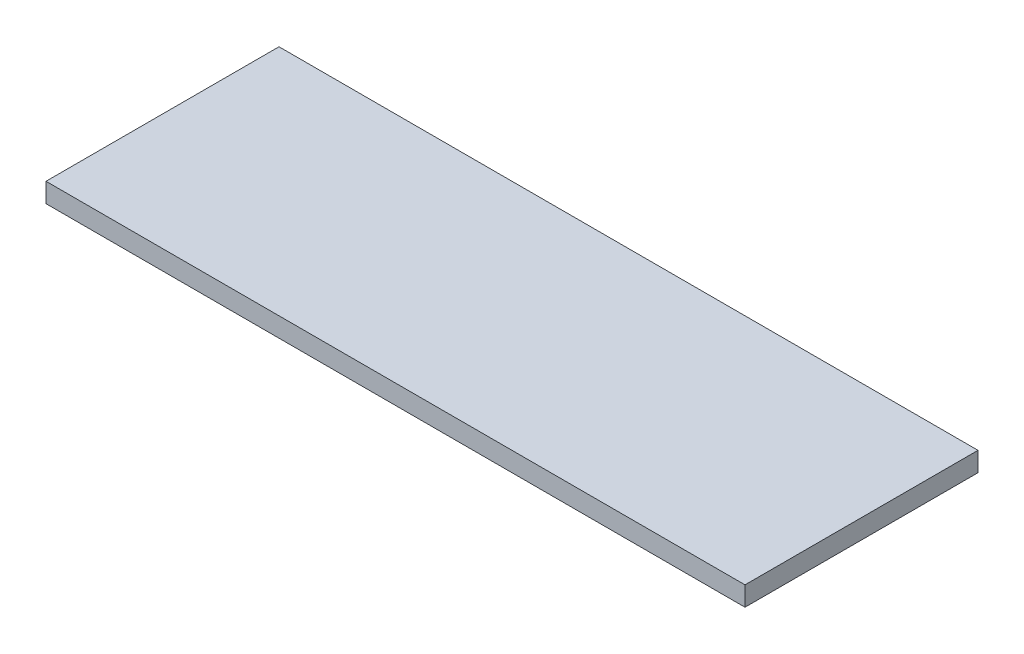
SolidWorks part; units mm, degrees
ref_plane "Front Plane" through (0, 0, 0) normal (0, 0, 1) x (1, 0, 0)
ref_plane "Top Plane" through (0, 0, 0) normal (0, 1, 0) x (1, 0, 0)
ref_plane "Right Plane" through (0, 0, 0) normal (1, 0, 0) x (0, 0, -1)
sketch "Sketch1" plane through (0, 0, 0) normal (0, 1, 0) x (1, 0, 0)
  line L1 (-457.2, -152.4) -> (457.2, -152.4)
  line L2 (-457.2, -152.4) -> (-457.2, 152.4)
  line L3 (-457.2, 152.4) -> (457.2, 152.4)
  line L4 (457.2, -152.4) -> (457.2, 152.4)
  line L5 (-457.2, -152.4) -> (457.2, 152.4) construction
  line L6 (-457.2, 152.4) -> (457.2, -152.4) construction
  point P0 (0, 0)
  dimension "D1" = 304.8
  dimension "D2" = 914.4
extrude "Boss-Extrude1" add sketch "Sketch1" along normal blind 25.4
